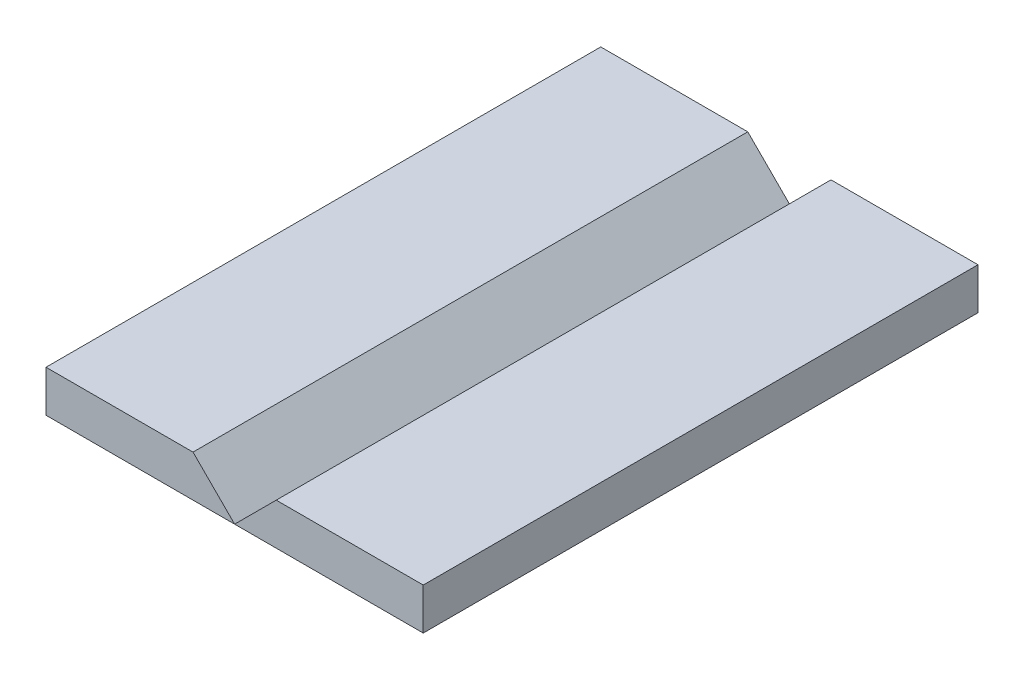
SolidWorks part; units mm, degrees
ref_plane "Front Plane" through (0, 0, 0) normal (0, 0, 1) x (1, 0, 0)
ref_plane "Top Plane" through (0, 0, 0) normal (0, 1, 0) x (1, 0, 0)
ref_plane "Right Plane" through (0, 0, 0) normal (1, 0, 0) x (0, 0, -1)
sketch "Sketch1" plane through (0, 0, 0) normal (0, 0, 1) x (1, 0, 0)
  line L0 (68, 0) -> (68, 15) construction
  line L1 (0, 0) -> (136, 0)
  line L2 (0, 0) -> (0, 15)
  line L3 (0, 15) -> (53, 15)
  line L5 (68, 0) -> (53, 15)
  line L6 (136, 0) -> (136, 15)
  line L7 (136, 15) -> (83, 15)
  line L8 (68, 0) -> (83, 15)
extrude "Boss-Extrude1" add sketch "Sketch1" along normal blind 200 contours L1 L5 L3 L2 | L8 L1 L6 L7
